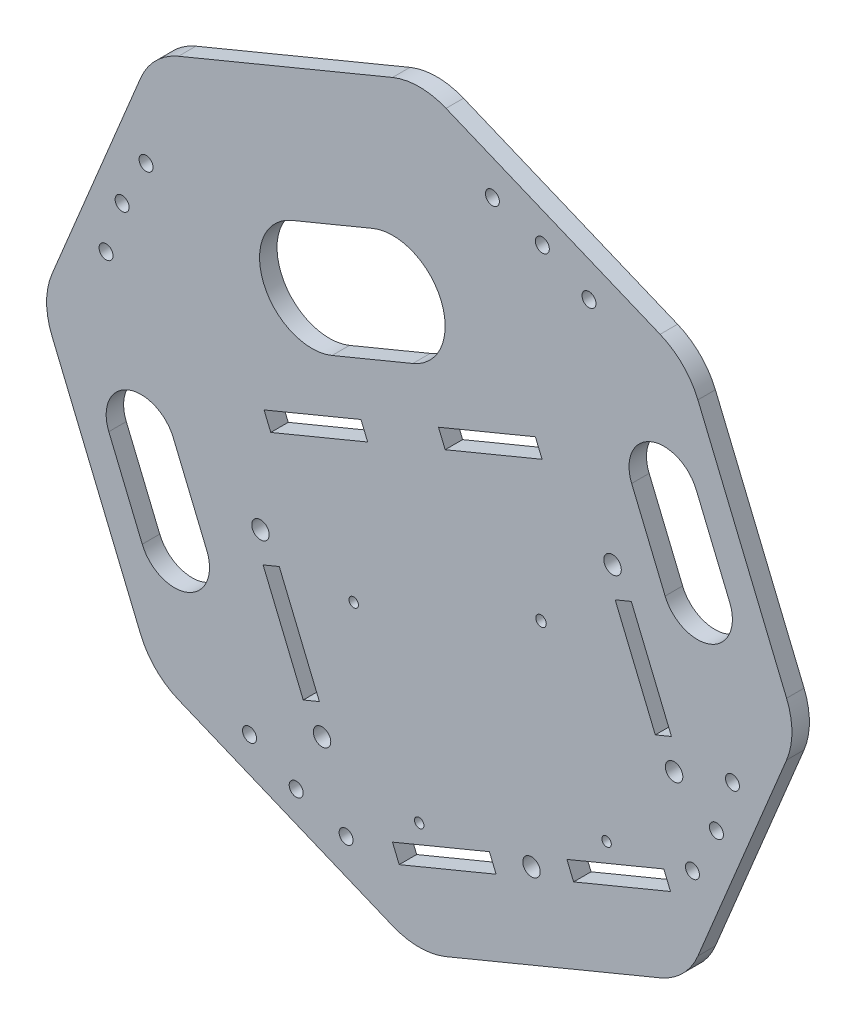
SolidWorks part; units mm, degrees
ref_plane "前视基准面" through (0, 0, 0) normal (0, 0, 1) x (1, 0, 0)
ref_plane "上视基准面" through (0, 0, 0) normal (0, 1, 0) x (1, 0, 0)
ref_plane "右视基准面" through (0, 0, 0) normal (1, 0, 0) x (0, 0, -1)
sketch "草图1" plane through (0, 0, 0) normal (0, 0, 1) x (1, 0, 0)
  line L0 (0, 121.5223) -> (0, -117.9323) construction
  line L1 (-126.6637, 0) -> (129.3981, 0) construction
  line L2 (0, 108.2392) -> (-76.5367, 76.5367)
  line L3 (-76.5367, 76.5367) -> (-108.2392, 0)
  line L4 (-108.2392, 0) -> (-76.5367, -76.5367)
  line L5 (-76.5367, -76.5367) -> (0, -108.2392)
  line L6 (0, -108.2392) -> (76.5367, -76.5367)
  line L7 (76.5367, -76.5367) -> (108.2392, 0)
  line L8 (108.2392, 0) -> (76.5367, 76.5367)
  line L9 (76.5367, 76.5367) -> (0, 108.2392)
  line L10 (-51.7164, -4.1034) -> (-16.8922, -88.1764) construction
  line L11 (-51.7164, -4.1034) -> (44.3671, 35.6957) construction
  line L12 (-16.8922, -88.1764) -> (79.1913, -48.3773) construction
  line L13 (44.3671, 35.6957) -> (79.1913, -48.3773) construction
  line L14 (-38.2683, -92.388) -> (38.2683, 92.388) construction
  line L15 (-92.388, 38.2683) -> (92.388, -38.2683) construction
  line L20 (-38.2683, 92.388) -> (0, 0) construction
  line L21 (-40.0445, -32.2817) -> (-28.564, -59.9981)
  line L22 (-40.0445, -32.2817) -> (-44.6639, -34.1951)
  line L23 (-28.564, -59.9981) -> (-33.1834, -61.9115)
  line L24 (-44.6639, -34.1951) -> (-33.1834, -61.9115)
  line L25 (-7.6534, -84.3496) -> (20.063, -72.8691)
  line L26 (-7.6534, -84.3496) -> (-5.74, -88.969)
  line L27 (20.063, -72.8691) -> (21.9764, -77.4885)
  line L28 (-5.74, -88.969) -> (21.9764, -77.4885)
  line L29 (56.0389, 7.5174) -> (67.5194, -20.199)
  line L30 (56.0389, 7.5174) -> (60.6583, 9.4308)
  line L31 (67.5194, -20.199) -> (72.1388, -18.2856)
  line L32 (60.6583, 9.4308) -> (72.1388, -18.2856)
  line L33 (-42.4776, -0.2765) -> (-14.7612, 11.204)
  line L34 (-42.4776, -0.2765) -> (-44.391, 4.3429)
  line L35 (-14.7612, 11.204) -> (-16.6746, 15.8234)
  line L36 (-44.391, 4.3429) -> (-16.6746, 15.8234)
  line L37 (42.2361, -63.6847) -> (69.9525, -52.2041)
  line L38 (42.2361, -63.6847) -> (44.1495, -68.3041)
  line L39 (69.9525, -52.2041) -> (71.8659, -56.8235)
  line L40 (44.1495, -68.3041) -> (71.8659, -56.8235)
  line L41 (7.4119, 20.3884) -> (35.1283, 31.8689)
  line L42 (7.4119, 20.3884) -> (5.4985, 25.0078)
  line L43 (35.1283, 31.8689) -> (33.2149, 36.4883)
  line L44 (5.4985, 25.0078) -> (33.2149, 36.4883)
  line L45 (-30.6827, 41.4104) -> (-7.5857, 50.9775) construction
  line L46 (-36.4229, 55.2686) -> (-13.3259, 64.8357)
  line L47 (-24.9424, 27.5522) -> (-1.8454, 37.1193)
  line L48 (-92.388, -38.2683) -> (92.388, 38.2683) construction
  line L49 (-79.5646, -19.4268) -> (-69.9975, -42.5238) construction
  line L50 (-70.3258, -15.6) -> (-60.7587, -38.697)
  line L51 (-88.8034, -23.2537) -> (-79.2363, -46.3506)
  line L52 (69.9975, 42.5238) -> (79.5646, 19.4268) construction
  line L53 (60.7587, 38.697) -> (70.3258, 15.6)
  line L54 (79.2363, 46.3506) -> (88.8034, 23.2537)
  line L55 (-18.7562, -30.4993) -> (-0.0047, -75.7694) construction
  line L56 (-18.7562, -30.4993) -> (34.8289, -8.3037) construction
  line L57 (-0.0047, -75.7694) -> (53.5803, -53.5737) construction
  line L58 (34.8289, -8.3037) -> (53.5803, -53.5737) construction
  circle A0 centre (0, 0) radius 100 construction
  circle A5 centre (-35.2069, -84.9969) radius 2
  circle A6 centre (84.9969, -35.2069) radius 2
  circle A7 centre (35.2069, 84.9969) radius 2
  circle A8 centre (-84.9969, 35.2069) radius 2
  circle A10 centre (-45.4157, -25.8474) radius 2.5
  circle A11 centre (-27.8123, -68.3458) radius 2.5
  circle A12 centre (55.2872, 15.8651) radius 2.5
  circle A13 centre (72.8906, -26.6333) radius 2.5
  circle A14 centre (32.1062, -70.5866) radius 2.5
  arc A15 (-36.4229, 55.2686) -> (-24.9424, 27.5522) centre (-30.6827, 41.4104) ccw
  arc A16 (-1.8454, 37.1193) -> (-13.3259, 64.8357) centre (-7.5857, 50.9775) ccw
  arc A17 (-70.3258, -15.6) -> (-88.8034, -23.2537) centre (-79.5646, -19.4268) ccw
  arc A18 (-79.2363, -46.3506) -> (-60.7587, -38.697) centre (-69.9975, -42.5238) ccw
  arc A19 (60.7587, 38.697) -> (79.2363, 46.3506) centre (69.9975, 42.5238) cw
  arc A20 (88.8034, 23.2537) -> (70.3258, 15.6) centre (79.5646, 19.4268) cw
  circle A21 centre (-18.7562, -30.4993) radius 1.35
  circle A22 centre (-0.0047, -75.7694) radius 1.35
  circle A23 centre (34.8289, -8.3037) radius 1.5
  circle A24 centre (53.5803, -53.5737) radius 1.35
  circle A25 centre (89.5883, -20.9269) radius 2
  circle A26 centre (-20.9269, -89.5883) radius 2
  circle A27 centre (-89.5883, 20.9269) radius 2
  circle A28 centre (20.9269, 89.5883) radius 2
  circle A29 centre (-48.551, -78.146) radius 2
  circle A30 centre (-78.146, 48.551) radius 2
  circle A31 centre (48.551, 78.146) radius 2
  circle A32 centre (78.146, -48.551) radius 2
  point P68 (-19.1342, 46.194)
  point P77 (-74.781, -30.9753)
  point P86 (74.781, 30.9753)
  point P108 (0, 0)
  point P117 (0, 0)
  dimension "D6" = 5
  dimension "D7" = 5
  dimension "D8" = 30
  dimension "D9" = 5
  dimension "D10" = 4
  dimension "D11" = 4
  dimension "D12" = 4
  dimension "D13" = 4
  dimension "D14" = 8
  dimension "D15" = 8
  dimension "D16" = 8
  dimension "D17" = 8
  dimension "D21" = 30.5
  dimension "D22" = 5
  dimension "D23" = 30
  dimension "D24" = 10
  dimension "D26" = 5
  dimension "D27" = 30
  dimension "D32" = 5
  dimension "D33" = 5
  dimension "D34" = 5
  dimension "D35" = 5
  dimension "D39" = 8
  dimension "D41" = 8
  dimension "D42" = 8
  dimension "D43" = 2.5
  dimension "D45" = 5
  dimension "D49" = 15
  dimension "D52" = 10
  dimension "D57" = 3
  dimension "D58" = 2.7
  dimension "D59" = 2.7
  dimension "D60" = 2.7
  dimension "D63" = 4
  dimension "D66" = 4
  dimension "D1" = 200
  dimension "D2" = 91
  dimension "D3" = 104
  dimension "D4" = 50.65
  dimension "D5" = 25
  dimension "D18" = 30
  dimension "D19" = 30
  dimension "D20" = 30.5
  dimension "D25" = 10
  dimension "D28" = 10
  dimension "D29" = 5
  dimension "D30" = 30
  dimension "D31" = 10
  dimension "D36" = 8
  dimension "D37" = 2.5
  dimension "D38" = 2.5
  dimension "D40" = 2.5
  dimension "D44" = 2.5
  dimension "D46" = 12
  dimension "D47" = 0
  dimension "D48" = 25
  dimension "D50" = 35
  dimension "D51" = 25
  dimension "D53" = 49
  dimension "D54" = 58
  dimension "D55" = 30
  dimension "D56" = 29
  dimension "D61" = 92
  dimension "D62" = 15
  dimension "D65" = 92
  dimension "D67" = 15
  dimension "D64" = 4
  dimension "D68" = 4
extrude "凸台-拉伸1" add sketch "草图1" along normal blind 5
fillet "圆角1" radius 20 8 edges at (-76.5367, 76.5367, 2.5) (0, 108.2392, 2.5) (76.5367, 76.5367, 2.5) (108.2392, 0, 2.5) (76.5367, -76.5367, 2.5) (0, -108.2392, 2.5) (-76.5367, -76.5367, 2.5) (-108.2392, 0, 2.5)
